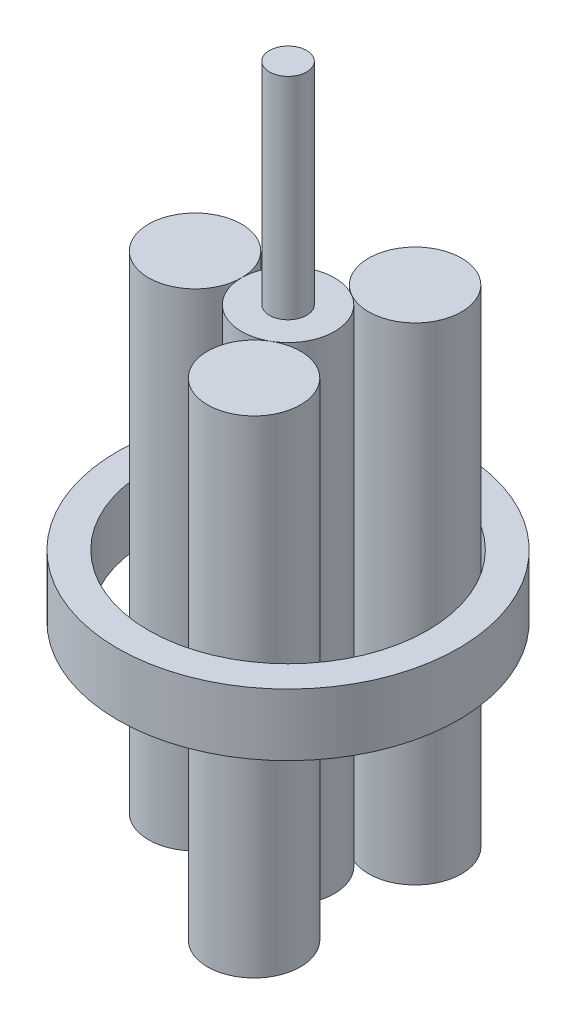
SolidWorks part; units mm, degrees
ref_plane "Front Plane" through (0, 0, 0) normal (0, 0, 1) x (1, 0, 0)
ref_plane "Top Plane" through (0, 0, 0) normal (0, 1, 0) x (1, 0, 0)
ref_plane "Right Plane" through (0, 0, 0) normal (1, 0, 0) x (0, 0, -1)
sketch "Sketch1" plane through (0, 0, 0) normal (0, 1, 0) x (1, 0, 0)
  line L0 (0, 0) -> (-54.6613, 0) construction
  line L1 (0, 0) -> (6.831, 11.8316) construction
  line L2 (0, 0) -> (42.8131, -74.1544) construction
  circle A0 centre (0, 0) radius 1.5
  circle A1 centre (-3, 0) radius 1.5
  circle A2 centre (1.5, 2.5981) radius 1.5
  circle A3 centre (1.5, -2.5981) radius 1.5
  dimension "D2" = 3
  dimension "D1" = 120
  dimension "D3" = 120
extrude "Boss-Extrude1" add sketch "Sketch1" along normal mid plane 15.7 contours A1 | A0 | A2 | A3
sketch "Sketch3" plane through (0, 0, 0) normal (0, 1, 0) x (1, 0, 0)
  circle A1 centre (0, 0) radius 4.5
  circle A2 centre (0, 0) radius 5.5
  circle A3 centre (-3, 0) radius 1.5 construction
  dimension "D1" = 1
extrude "Boss-Extrude2" add sketch "Sketch3" along normal mid plane 2 separate body
sketch "Sketch4" plane through (0, 7.85, 0) normal (0, 1, 0) x (1, 0, 0)
  circle A0 centre (0, 0) radius 0.6
  dimension "D1" = 1.2
extrude "Boss-Extrude3" add sketch "Sketch4" along normal blind 6.8
